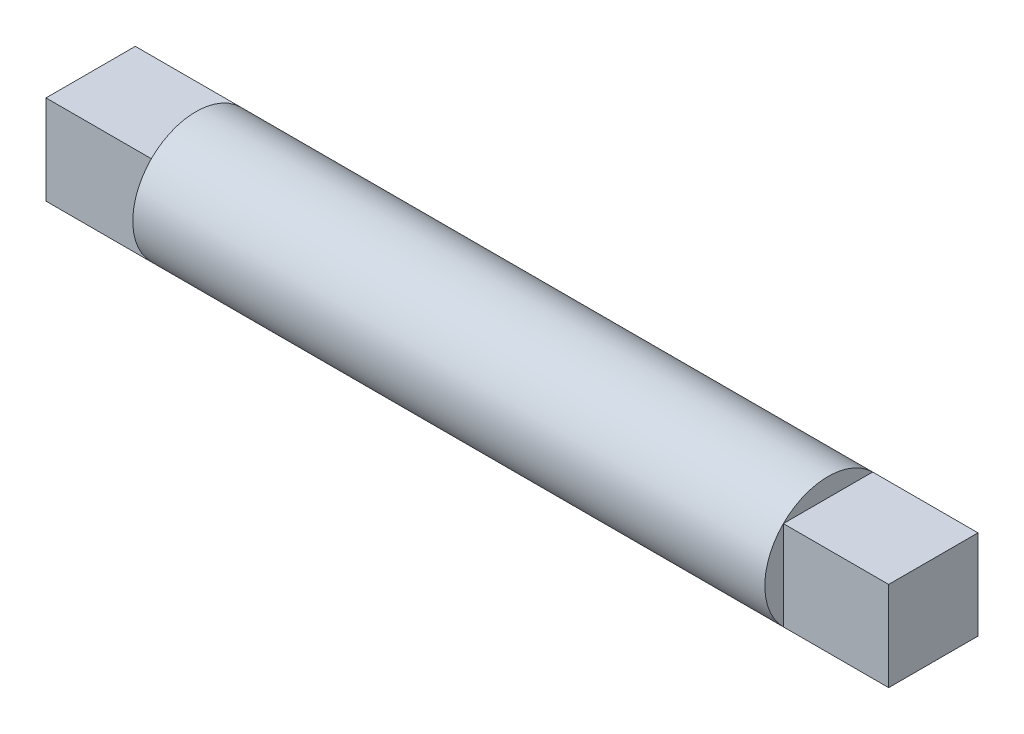
SolidWorks part; units mm, degrees
ref_plane "Front Plane" through (0, 0, 0) normal (0, 0, 1) x (1, 0, 0)
ref_plane "Top Plane" through (0, 0, 0) normal (0, 1, 0) x (1, 0, 0)
ref_plane "Right Plane" through (0, 0, 0) normal (1, 0, 0) x (0, 0, -1)
sketch "Sketch1" plane through (0, 0, 0) normal (1, 0, 0) x (0, 0, -1)
  circle A0 centre (0, 0) radius 3
  dimension "D1" = 6
extrude "Boss-Extrude1" add sketch "Sketch1" along normal blind 15
sketch "Sketch2" plane through (15, 0, 0) normal (1, 0, 0) x (0, 0, -1)
  line L1 (-2.12, 2.1226) -> (2.12, 2.1226)
  line L2 (-2.12, 2.1226) -> (-2.12, -2.1226)
  line L3 (-2.12, -2.1226) -> (2.12, -2.1226)
  line L4 (2.12, 2.1226) -> (2.12, -2.1226)
  line L5 (-2.12, 2.1226) -> (2.12, -2.1226) construction
  line L6 (-2.12, -2.1226) -> (2.12, 2.1226) construction
  circle A0 centre (0, 0) radius 3 construction
  point P0 (0, 0)
  dimension "D1" = 4.24
extrude "Boss-Extrude2" add sketch "Sketch2" along normal blind 5
mirror "Mirror1" about plane through (0, 0, 0) normal (1, 0, 0) of "Boss-Extrude2", "Boss-Extrude1"
